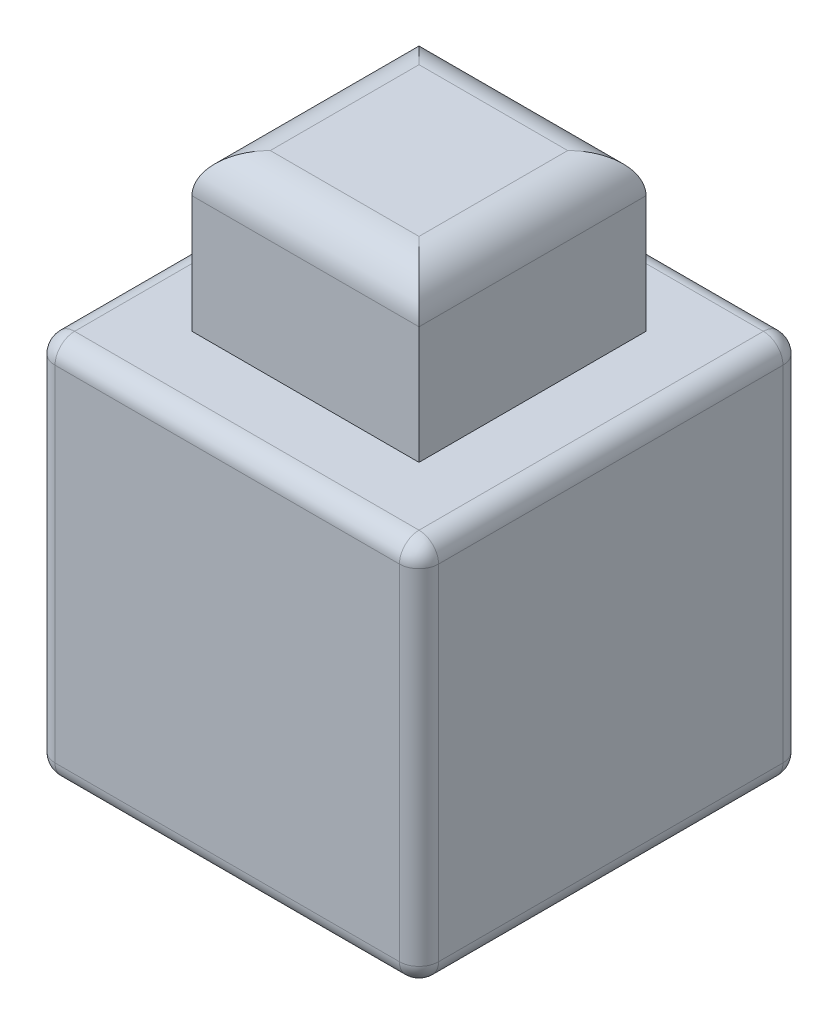
SolidWorks part; units mm, degrees
ref_plane "Front Plane" through (0, 0, 0) normal (0, 0, 1) x (1, 0, 0)
ref_plane "Top Plane" through (0, 0, 0) normal (0, 1, 0) x (1, 0, 0)
ref_plane "Right Plane" through (0, 0, 0) normal (1, 0, 0) x (0, 0, -1)
sketch "Sketch2" plane through (0, 0, 0) normal (0, 0, 1) x (1, 0, 0)
  line L1 (-4.9, 4.9) -> (4.9, 4.9)
  line L2 (-4.9, 4.9) -> (-4.9, -4.9)
  line L3 (-4.9, -4.9) -> (4.9, -4.9)
  line L4 (4.9, 4.9) -> (4.9, -4.9)
  point P0 (0, 0)
  dimension "D1" = 9.8
  dimension "D2" = 9.8
extrude "Boss-Extrude1" add sketch "Sketch2" against normal blind 9.8
ref_plane "Plane1" through (0, 4.9, 0) normal (0, 1, 0) x (1, 0, 0)
sketch "Sketch3" plane through (0, 4.9, 0) normal (0, 1, 0) x (1, 0, 0)
  line L3 (-2.9, 7.8) -> (2.9, 7.8)
  line L4 (-2.9, 7.8) -> (-2.9, 2)
  line L5 (-2.9, 2) -> (2.9, 2)
  line L6 (2.9, 7.8) -> (2.9, 2)
  dimension "D1" = 5.8
  dimension "D2" = 5.8
extrude "Boss-Extrude2" add sketch "Sketch3" along normal blind 4
fillet "Fillet3" radius 1 4 edges at (0, 8.9, -7.8) (-2.9, 8.9, -4.9) (0, 8.9, -2) (2.9, 8.9, -4.9)
fillet "Fillet4" radius 0.5 12 edges at (-4.9, 4.9, -4.9) (0, 4.9, -9.8) (-4.9, 0, -9.8) (4.9, 4.9, -4.9) (4.9, 0, -9.8) (-4.9, 0, 0) (0, 4.9, 0) (4.9, 0, 0) (4.9, -4.9, -4.9) (0, -4.9, -9.8) (-4.9, -4.9, -4.9) (0, -4.9, 0)
